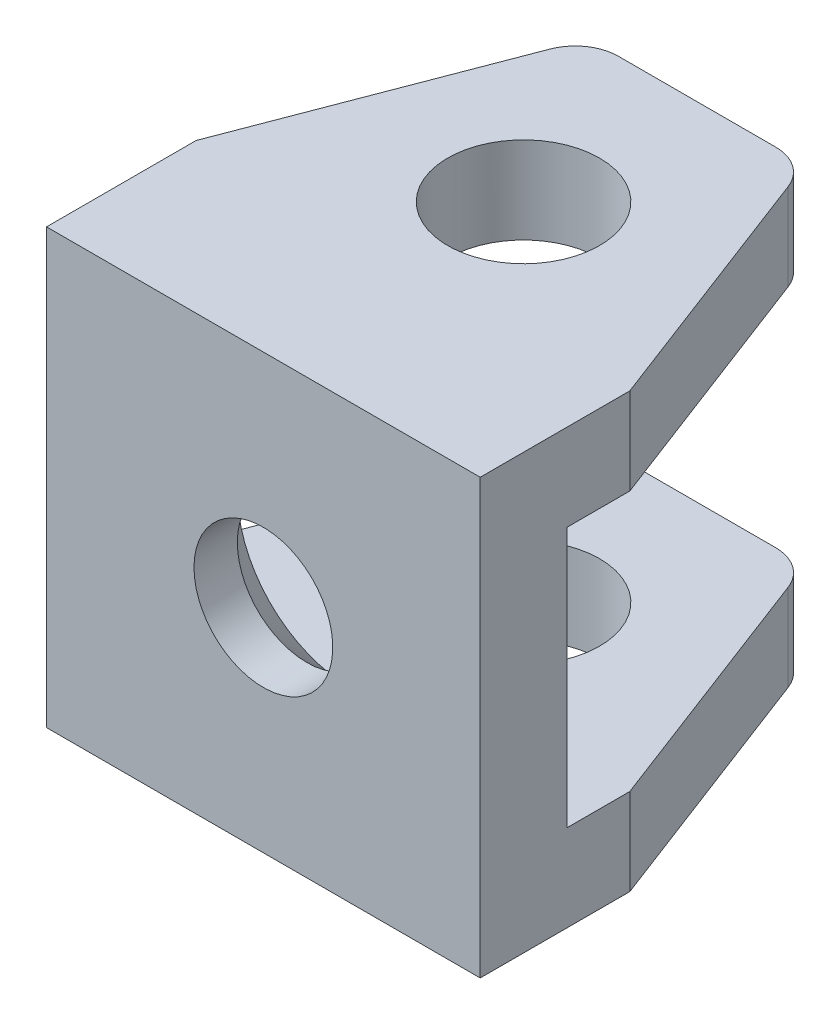
SolidWorks part; units mm, degrees
ref_plane "前视基准面" through (0, 0, 0) normal (0, 0, 1) x (1, 0, 0)
ref_plane "上视基准面" through (0, 0, 0) normal (0, 1, 0) x (1, 0, 0)
ref_plane "右视基准面" through (0, 0, 0) normal (1, 0, 0) x (0, 0, -1)
other "Configuration Table"
sketch "草图1" plane through (0, 0, 0) normal (0, 1, 0) x (1, 0, 0)
  line L0 (-2.5, 5) -> (-5, -1.5509)
  line L1 (-5, -5) -> (5, -5)
  line L2 (-5, -5) -> (-5, -1.5509)
  line L3 (-2.5, 5) -> (2.5, 5)
  line L4 (5, -5) -> (5, -1.5509)
  line L5 (-5, -5) -> (3.1905, 3.1905) construction
  line L6 (-3.1905, 3.1905) -> (5, -5) construction
  line L7 (0, 0) -> (0, 50000) construction
  line L8 (2.5, 5) -> (5, -1.5509)
  point P0 (0, 0)
  dimension "D1" = 10
  dimension "D3" = 6.5509
  dimension "D4" = 2.5
extrude "凸台-拉伸1" add sketch "草图1" along normal blind 10
sketch "草图2" plane through (5, 0, 0) normal (1, 0, 0) x (0, 0, -1)
  line L0 (5, 5) -> (-49995, 5) construction
  line L1 (5, 10) -> (5, 0) construction
  line L2 (-1.5509, 10) -> (-1.5509, 0) construction
  line L3 (5, 2) -> (5, 8)
  line L4 (5, 8) -> (-3, 8)
  line L5 (-3, 8) -> (-3, 2)
  line L6 (-1.5509, 10) -> (5, 10) construction
  line L7 (-5, 10) -> (-5, 0) construction
  line L8 (5, 2) -> (-3, 2)
  point P4 (5, 5)
  point P7 (-1.5509, 5)
  point P17 (-3, 5)
  point P18 (5, 5)
  dimension "D1" = 2
  dimension "D2" = 2
extrude "切除-拉伸1" cut sketch "草图2" against normal blind 10
sketch "草图3" plane through (0, 0, 0) normal (0, -1, 0) x (1, 0, 0)
  circle A0 centre (0, -1) radius 1.75
  dimension "D2" = 3.5
  dimension "D1" = 1
extrude "切除-拉伸2" cut sketch "草图3" against normal blind 10
fillet "圆角1" radius 1 4 edges at (-2.5, 9, -5) (2.5, 9, -5) (-2.5, 1, -5) (2.5, 1, -5)
sketch "草图4" plane through (0, 0, 3) normal (0, 0, -1) x (-1, 0, 0)
  line L0 (-5, 5) -> (49985.1651, -986.6632) construction
  line L1 (-5, 8) -> (-5, 2) construction
  circle A0 centre (0, 4.9008) radius 1.6
  point P6 (-5, 5)
  dimension "D1" = 3.2
extrude "切除-拉伸3" cut sketch "草图4" against normal blind 10
chamfer "倒角1" distance 1 angle 45 1 edges at (-1.6, 4.9008, 3)
